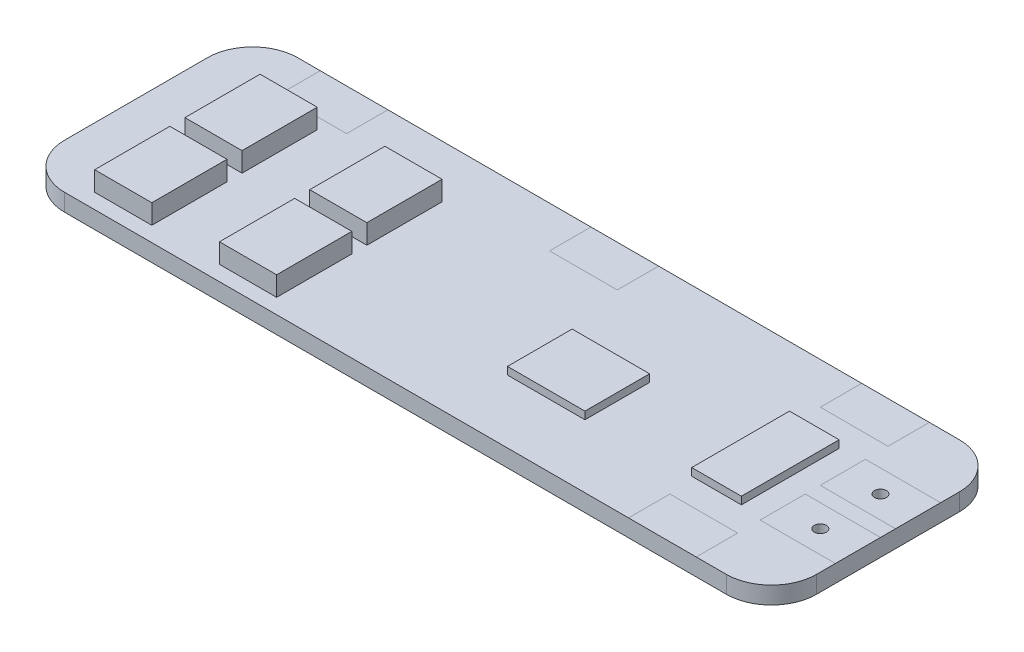
SolidWorks part; units mm, degrees
ref_plane "Alzado" through (0, 0, 0) normal (0, 0, 1) x (1, 0, 0)
ref_plane "Planta" through (0, 0, 0) normal (0, 1, 0) x (1, 0, 0)
ref_plane "Vista lateral" through (0, 0, 0) normal (1, 0, 0) x (0, 0, -1)
sketch "Croquis1" plane through (0, 0, 0) normal (0, 1, 0) x (1, 0, 0)
  line L0 (25, 0) -> (-25, 0) construction
  line L1 (-22, 7.75) -> (22, 7.75)
  line L2 (-25, 4.75) -> (-25, -4.75)
  line L3 (-22, -7.75) -> (22, -7.75)
  line L4 (25, 4.75) -> (25, -4.75)
  line L5 (-25, 7.75) -> (25, -7.75) construction
  line L6 (-25, -7.75) -> (25, 7.75) construction
  circle A0 centre (22.5, 2) radius 0.4
  circle A1 centre (22.5, -2) radius 0.4
  arc A2 (22, -7.75) -> (25, -4.75) centre (22, -4.75) ccw
  arc A3 (-25, -4.75) -> (-22, -7.75) centre (-22, -4.75) ccw
  arc A4 (-22, 7.75) -> (-25, 4.75) centre (-22, 4.75) ccw
  arc A5 (22, 7.75) -> (25, 4.75) centre (22, 4.75) cw
  point P0 (0, 0)
  point P9 (0, 0)
  dimension "D4" = 0.8
  dimension "D6" = 3
  dimension "D1" = 50
  dimension "D2" = 15.5
  dimension "D3" = 2.5
  dimension "D5" = 2
extrude "Saliente-Extruir1" add sketch "Croquis1" along normal blind 1.15
sketch "Croquis2" plane through (0, 1.15, 0) normal (0, 1, 0) x (1, 0, 0)
  line L0 (-25, -1.25) -> (25, -1.25) construction
  line L1 (-25, 4.75) -> (-25, -4.75) construction
  line L2 (25, -4.75) -> (25, 4.75) construction
  line L3 (-14.95, 7.75) -> (-14.95, -7.75) construction
  line L4 (-21, 4.25) -> (-17.2, 4.25)
  line L5 (-21, 4.25) -> (-21, -0.75)
  line L6 (-21, -0.75) -> (-17.2, -0.75)
  line L7 (-17.2, 4.25) -> (-17.2, -0.75)
  line L8 (22, 7.75) -> (-22, 7.75) construction
  line L9 (-22, -7.75) -> (22, -7.75) construction
  line L10 (-8.9, -0.75) -> (-12.7, -0.75)
  line L11 (-12.7, 4.25) -> (-12.7, -0.75)
  line L12 (-8.9, 4.25) -> (-12.7, 4.25)
  line L13 (-8.9, 4.25) -> (-8.9, -0.75)
  line L14 (-8.9, -6.75) -> (-8.9, -1.75)
  line L15 (-8.9, -6.75) -> (-12.7, -6.75)
  line L16 (-12.7, -6.75) -> (-12.7, -1.75)
  line L17 (-8.9, -1.75) -> (-12.7, -1.75)
  line L18 (-21, -1.75) -> (-17.2, -1.75)
  line L19 (-17.2, -6.75) -> (-17.2, -1.75)
  line L20 (-21, -6.75) -> (-17.2, -6.75)
  line L21 (-21, -6.75) -> (-21, -1.75)
  dimension "D1" = 3.8
  dimension "D2" = 5
  dimension "D3" = 4
  dimension "D4" = 2.25
  dimension "D5" = 3.5
  dimension "D6" = 0.5
extrude "Saliente-Extruir2" add sketch "Croquis2" along normal blind 1.3 separate body
sketch "Croquis3" plane through (0, 1.15, 0) normal (0, 1, 0) x (1, 0, 0)
  line L0 (22, 7.75) -> (-22, 7.75) construction
  line L1 (3.25, 0.75) -> (8.4, 0.75)
  line L2 (3.25, 0.75) -> (3.25, -3.55)
  line L3 (3.25, -3.55) -> (8.4, -3.55)
  line L4 (8.4, 0.75) -> (8.4, -3.55)
  line L5 (25, -4.75) -> (25, 4.75) construction
  line L7 (15.2, 3.25) -> (18.5, 3.25)
  line L8 (15.2, 3.25) -> (15.2, -3.25)
  line L9 (15.2, -3.25) -> (18.5, -3.25)
  line L10 (18.5, 3.25) -> (18.5, -3.25)
  point P12 (18.5, 0)
  dimension "D1" = 5.15
  dimension "D2" = 4.3
  dimension "D3" = 7
  dimension "D4" = 16.6
  dimension "D5" = 3.3
  dimension "D6" = 6.5
  dimension "D7" = 6.5
extrude "Saliente-Extruir3" add sketch "Croquis3" along normal blind 0.5 separate body
sketch "Croquis4" plane through (0, 1.15, 0) normal (0, 1, 0) x (1, 0, 0)
  line L0 (25, -4.75) -> (25, 4.75) construction
  line L1 (20, 3.5) -> (25, 3.5)
  line L2 (20, 3.5) -> (20, 0.5)
  line L3 (20, 0.5) -> (25, 0.5)
  line L4 (25, 3.5) -> (25, 0.5)
  line L5 (20, 3.5) -> (25, 0.5) construction
  line L6 (20, 0.5) -> (25, 3.5) construction
  line L7 (25, 0) -> (-25, 0) construction
  line L8 (-25, 4.75) -> (-25, -4.75) construction
  line L9 (22, 7.75) -> (-22, 7.75) construction
  line L10 (15.5, 7.75) -> (20, 7.75)
  line L11 (15.5, 7.75) -> (15.5, 5)
  line L12 (15.5, 5) -> (20, 5)
  line L13 (20, 7.75) -> (20, 5)
  line L14 (-2.5, 7.75) -> (-2.5, 5)
  line L15 (-2.5, 7.75) -> (2, 7.75)
  line L16 (2, 7.75) -> (2, 5)
  line L17 (-2.5, 5) -> (2, 5)
  line L18 (-20.5, 7.75) -> (-20.5, 5)
  line L19 (-20.5, 7.75) -> (-16, 7.75)
  line L20 (-16, 7.75) -> (-16, 5)
  line L21 (-20.5, 5) -> (-16, 5)
  line L22 (15.5, -5) -> (20, -5)
  line L23 (20, -7.75) -> (20, -5)
  line L24 (15.5, -7.75) -> (20, -7.75)
  line L25 (15.5, -7.75) -> (15.5, -5)
  line L26 (20, -0.5) -> (25, -0.5)
  line L27 (25, -3.5) -> (25, -0.5)
  line L28 (20, -3.5) -> (25, -3.5)
  line L29 (20, -3.5) -> (20, -0.5)
  point P0 (22.5, 2)
  point P14 (0, 0)
  dimension "D1" = 3
  dimension "D2" = 4.5
  dimension "D3" = 2.75
  dimension "D5" = 13.5
  dimension "D4" = 3
split line "Línea de partición1"
